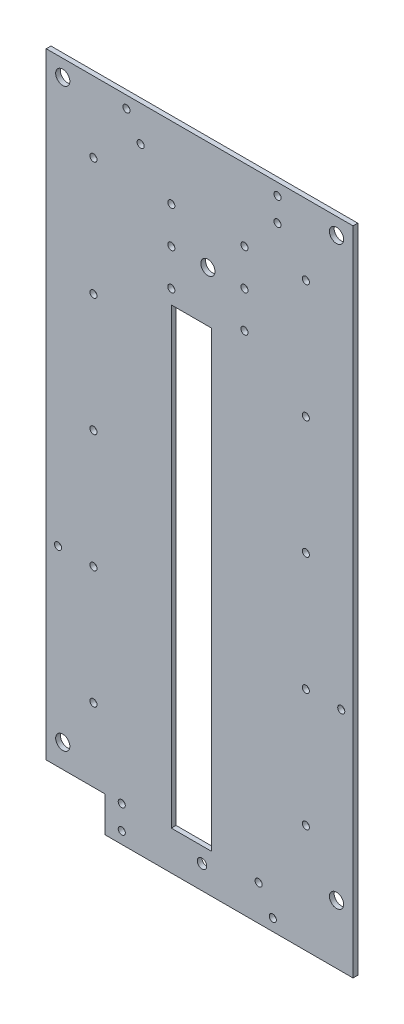
SolidWorks part; units mm, degrees
ref_plane "Plan de face" through (0, 0, 0) normal (0, 0, 1) x (1, 0, 0)
ref_plane "Plan de dessus" through (0, 0, 0) normal (0, 1, 0) x (1, 0, 0)
ref_plane "Plan de droite" through (0, 0, 0) normal (1, 0, 0) x (0, 0, -1)
sketch "Esquisse1" plane through (0, 0, 0) normal (0, 0, 1) x (1, 0, 0)
  line L0 (1.9325, -483.3822) -> (106.9325, -483.3822)
  line L1 (-23.0675, -207.3822) -> (106.9325, -207.3822)
  line L2 (-23.0675, -207.3822) -> (-23.0675, -468.3822)
  line L3 (29.9325, -253.3822) -> (60.9325, -253.3822) construction
  line L4 (106.9325, -207.3822) -> (106.9325, -483.3822)
  line L5 (29.9325, -274.8822) -> (46.9325, -274.8822)
  line L6 (29.9325, -274.8822) -> (29.9325, -466.8822)
  line L7 (29.9325, -466.8822) -> (46.9325, -466.8822)
  line L8 (46.9325, -274.8822) -> (46.9325, -466.8822)
  line L9 (34.9575, -204.8822) -> (34.9575, -425.9806) construction
  line L12 (41.9325, -231.0772) -> (41.9325, -248.1373) construction
  line L13 (8.9325, -468.3822) -> (8.9325, -478.3822) construction
  line L17 (-23.0675, -468.3822) -> (1.9325, -468.3822)
  line L18 (1.9325, -483.3822) -> (1.9325, -468.3822)
  line L33 (29.9325, -268.8822) -> (29.9325, -237.8822) construction
  line L34 (29.9325, -268.8822) -> (60.9325, -268.8822) construction
  line L35 (60.9325, -268.8822) -> (60.9325, -237.8822) construction
  line L36 (29.9325, -237.8822) -> (60.9325, -237.8822) construction
  circle A0 centre (-16.0675, -214.3822) radius 3
  circle A1 centre (8.9325, -468.3822) radius 1.5
  circle A2 centre (10.9325, -212.3822) radius 1.5
  circle A3 centre (8.9325, -478.3822) radius 1.5
  circle A4 centre (60.9325, -268.8822) radius 1.5
  circle A5 centre (29.9325, -268.8822) radius 1.5
  circle A6 centre (29.9325, -237.8822) radius 1.5
  circle A7 centre (60.9325, -237.8822) radius 1.5
  circle A8 centre (29.9325, -253.3822) radius 1.5
  circle A9 centre (60.9325, -253.3822) radius 1.5
  circle A10 centre (16.9325, -222.3822) radius 1.5
  circle A11 centre (72.9325, -478.3822) radius 1.5
  circle A12 centre (45.4325, -253.3822) radius 3
  circle A13 centre (66.9325, -468.3822) radius 1.5
  circle A14 centre (74.9325, -222.3822) radius 1.5
  circle A15 centre (99.9325, -214.3822) radius 3
  circle A16 centre (74.9325, -212.3822) radius 1.5
  circle A20 centre (-16.0675, -458.3822) radius 3
  circle A21 centre (99.9325, -458.3822) radius 3
  dimension "D3" = 7
  dimension "D5" = 244
  dimension "D12" = 276
  dimension "D13" = 65
  dimension "D17" = 30.5
  dimension "D18" = 31
  dimension "D23" = 15
  dimension "D16" = 15
  dimension "D26" = 32
  dimension "D30" = 40
  dimension "D29" = 40
  dimension "D32" = 34
  dimension "D11" = 5
  dimension "D20" = 244
  dimension "D25" = 25
  dimension "D27" = 32
  dimension "D1" = 130
  dimension "D4" = 7
  dimension "D6" = 34
  dimension "D7" = 17
  dimension "D8" = 53
  dimension "D9" = 53
  dimension "D10" = 192
  dimension "D14" = 15
  dimension "D15" = 67.5
  dimension "D22" = 5
  dimension "D28" = 31
  dimension "D33" = 5
  dimension "D34" = 10
  dimension "D35" = 5
  dimension "D36" = 15
  dimension "D37" = 32
  dimension "D38" = 32
  dimension "D39" = 58.025
extrude "Extrusion1" add sketch "Esquisse1" along normal blind 2
sketch "Esquisse3" plane through (0, 0, 2) normal (0, 0, 1) x (1, 0, 0)
  line L0 (-3.0675, -237.3822) -> (-3.0675, -437.3822) construction
  line L1 (106.9325, -207.3822) -> (-23.0675, -207.3822) construction
  line L2 (-23.0675, -207.3822) -> (-23.0675, -468.3822) construction
  line L3 (86.9325, -237.3822) -> (86.9325, -437.3822) construction
  line L4 (106.9325, -483.3822) -> (106.9325, -207.3822) construction
  circle A0 centre (-3.0675, -237.3822) radius 1.5
  circle A1 centre (86.9325, -237.3822) radius 1.5
  circle A2 centre (86.9325, -437.3822) radius 1.5
  circle A3 centre (-3.0675, -437.3822) radius 1.5
  circle A4 centre (-3.0675, -337.3822) radius 1.5
  circle A5 centre (86.9325, -337.3822) radius 1.5
  circle A6 centre (-3.0675, -287.3822) radius 1.5
  circle A7 centre (86.9325, -287.3822) radius 1.5
  circle A8 centre (-3.0675, -387.3822) radius 1.5
  circle A9 centre (86.9325, -387.3822) radius 1.5
  circle A10 centre (42.9325, -473.3822) radius 2
  circle A11 centre (8.9325, -478.3822) radius 1.5 construction
  circle A12 centre (-18.0675, -203.3822) radius 1.5
  circle A13 centre (101.9325, -203.3822) radius 1.5
  circle A14 centre (-18.0675, -387.3822) radius 1.5
  circle A15 centre (101.9325, -387.3822) radius 1.5
  dimension "D7" = 50
  dimension "D11" = 5
  dimension "D13" = 5
  dimension "D15" = 15
  dimension "D16" = 15
  dimension "D1" = 200
  dimension "D2" = 30
  dimension "D3" = 20
  dimension "D4" = 200
  dimension "D5" = 30
  dimension "D6" = 20
  dimension "D8" = 50
  dimension "D9" = 50
  dimension "D10" = 50
  dimension "D12" = 34
  dimension "D14" = 5
extrude "Extrusion2" cut sketch "Esquisse3" against normal blind 10
